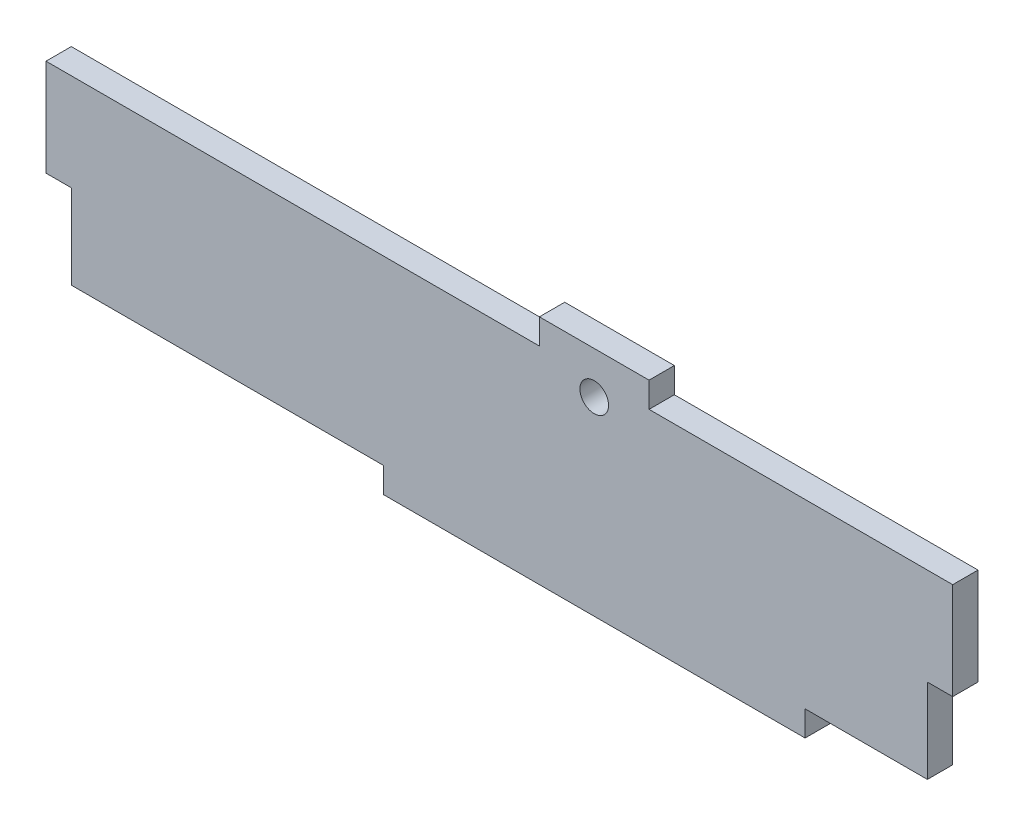
SolidWorks part; units mm, degrees
ref_plane "Front Plane" through (0, 0, 0) normal (0, 0, 1) x (1, 0, 0)
ref_plane "Top Plane" through (0, 0, 0) normal (0, 1, 0) x (1, 0, 0)
ref_plane "Right Plane" through (0, 0, 0) normal (1, 0, 0) x (0, 0, -1)
sketch "Sketch1" plane through (0, 0, 0) normal (0, 0, 1) x (1, 0, 0)
  line L0 (85, -34.6676) -> (85, 34.6676) construction
  line L1 (-130, 0) -> (85, 0)
  line L2 (-130, 0) -> (-130, 49)
  line L3 (-130, 49) -> (85, 49)
  line L4 (85, 0) -> (85, 49)
  line L5 (-124, 49) -> (-130, 49) construction
extrude "Boss-Extrude1" add sketch "Sketch1" along normal blind 6
sketch "Sketch2" plane through (0, 0, 0) normal (0, 0, -1) x (-1, 0, 0)
  line L0 (13, 43) -> (130, 43) construction
  line L1 (-85, 49) -> (-13, 49)
  line L2 (-85, 49) -> (-85, 43)
  line L3 (-85, 43) -> (-13, 43)
  line L4 (-13, 49) -> (-13, 43)
  line L6 (13, 49) -> (130, 49)
  line L7 (13, 49) -> (13, 43)
  line L8 (13, 43) -> (130, 43)
  line L9 (130, 49) -> (130, 43)
  line L10 (-85, 49) -> (130, 49) construction
  line L11 (-85, 34.6676) -> (-85, -34.6676) construction
  dimension "D1" = 13
  dimension "D2" = 26
extrude "Cut-Extrude1" cut sketch "Sketch2" against normal up to next
hole_wizard "M8x1.25 Tapped Hole1" positions "Sketch3" profile "Sketch4" tap size "M8x1.25" standard "ANSI Metric" end condition through all
sketch "Sketch3" plane through (0, 0, 0) normal (0, 0, -1) x (-1, 0, 0)
  point P0 (0, 39)
sketch "Sketch4" plane through (0, 39, 0) normal (1, 0, 0) x (0, 1, 0)
  line L0 (0, 0) -> (0, 6)
  line L1 (0, 6) -> (3.4, 6)
  line L2 (3.4, 6) -> (3.4, 0)
  line L5 (3.4, 0) -> (0, 0)
  line L11 (0, -6.35) -> (0, 107.95) construction
  dimension "Thread Major Dia." = 6.8
  dimension "Thru Tap Drill Depth" = 6
sketch "Sketch5" plane through (0, 0, 0) normal (0, 0, -1) x (-1, 0, 0)
  line L0 (-85, 20) -> (-85, 0) construction
  line L1 (-85, 0) -> (-79, 0)
  line L2 (-85, 0) -> (-85, 20)
  line L3 (-85, 20) -> (-79, 20)
  line L4 (-79, 0) -> (-79, 20)
  line L5 (-79, 20) -> (-79, 0) construction
  line L6 (124, 0) -> (124, 20) construction
  line L7 (130, 0) -> (124, 0)
  line L8 (130, 0) -> (130, 20)
  line L9 (130, 20) -> (124, 20)
  line L10 (124, 0) -> (124, 20)
  line L11 (-83.5008, 0) -> (-80.4992, 0) construction
  dimension "D1" = 20
extrude "Cut-Extrude2" cut sketch "Sketch5" against normal up to next
sketch "Sketch6" plane through (0, 0, 0) normal (0, 0, -1) x (-1, 0, 0)
  line L0 (-90, -6) -> (-50.05, -6) construction
  line L1 (-50, 0) -> (50, 0)
  line L2 (-50, 0) -> (-50, -6)
  line L3 (-50, -6) -> (50, -6)
  line L4 (50, 0) -> (50, -6)
  point P4 (0, 0)
  dimension "D1" = 100
extrude "Boss-Extrude2" add sketch "Sketch6" against normal blind 6
